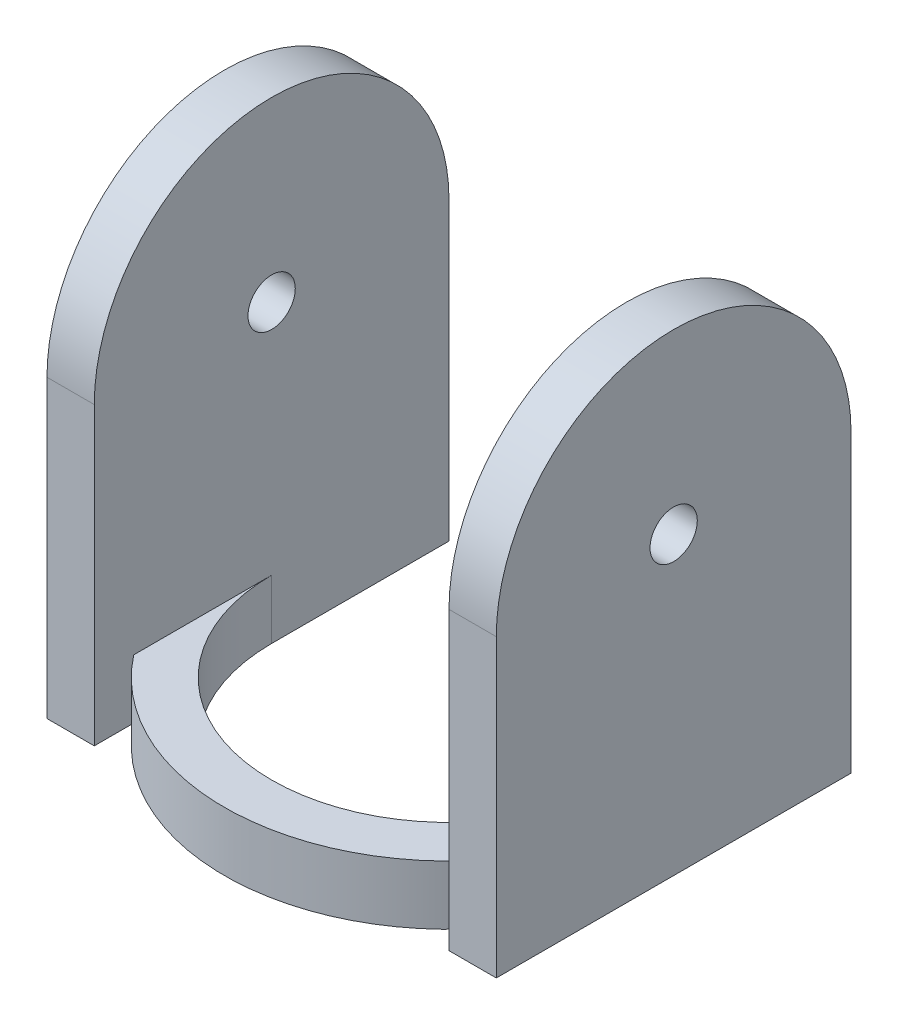
SolidWorks part; units mm, degrees
ref_plane "Front" through (0, 0, 0) normal (0, 0, 1) x (1, 0, 0)
ref_plane "Top" through (0, 0, 0) normal (0, 1, 0) x (1, 0, 0)
ref_plane "Right" through (0, 0, 0) normal (1, 0, 0) x (0, 0, -1)
sketch "草图1" plane through (0, 0, 0) normal (0, 1, 0) x (1, 0, 0)
  circle A0 centre (0, 0) radius 38
  circle A1 centre (0, 0) radius 30
extrude "凸台-拉伸1" add sketch "草图1" along normal blind 10
sketch "草图2" plane through (0, 0, 0) normal (0, -1, 0) x (1, 0, 0)
  line L0 (-38, 0) -> (0, 0) construction
  line L1 (0, 0) -> (0, 38) construction
  line L3 (-38, 30) -> (-30, 30)
  line L4 (-38, 30) -> (-38, -30)
  line L5 (-38, -30) -> (-30, -30)
  line L6 (-30, 30) -> (-30, -30)
  line L7 (38, 30) -> (30, 30)
  line L8 (38, 30) -> (38, -30)
  line L9 (38, -30) -> (30, -30)
  line L10 (30, 30) -> (30, -30)
  circle A0 centre (0, 0) radius 38 construction
  dimension "D1" = 60
  dimension "D2" = 30
  dimension "D3" = 8
  dimension "D4" = 38
  dimension "D5" = 60
  dimension "D6" = 30
  dimension "D7" = 8
extrude "凸台-拉伸2" add sketch "草图2" against normal blind 80
sketch "草图3" plane through (38, 0, 0) normal (1, 0, 0) x (0, 0, -1)
  line L0 (-30, 50) -> (-30, 88)
  line L1 (-30, 88) -> (30, 88)
  line L2 (30, 88) -> (30, 50)
  arc A0 (30, 50) -> (-30, 50) centre (0, 50) ccw
  circle A1 centre (0, 50) radius 4
  dimension "D1" = 38
extrude "切除-拉伸1" cut sketch "草图3" against normal blind 80
sketch "草图4" plane through (0, 0, 0) normal (0, -1, 0) x (1, 0, 0)
  line L1 (-30, 0) -> (30, 0)
  line L2 (-30, 0) -> (-30, -40.6781)
  line L3 (-30, -40.6781) -> (30, -40.6781)
  line L4 (30, 0) -> (30, -40.6781)
extrude "切除-拉伸2" cut sketch "草图4" against normal through all
